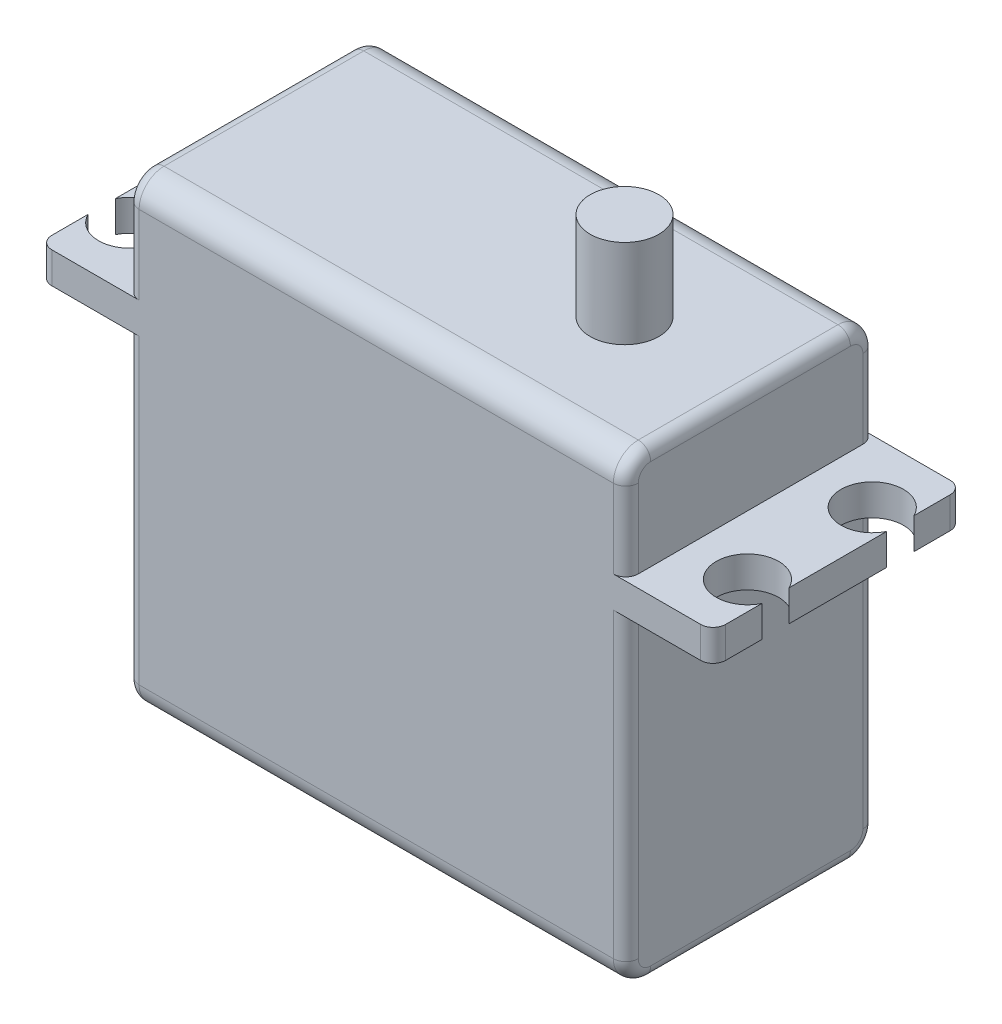
SolidWorks part; units mm, degrees
ref_plane "Front Plane" through (0, 0, 0) normal (0, 0, 1) x (1, 0, 0)
ref_plane "Top Plane" through (0, 0, 0) normal (0, 1, 0) x (1, 0, 0)
ref_plane "Right Plane" through (0, 0, 0) normal (1, 0, 0) x (0, 0, -1)
sketch "Sketch2" plane through (0, 0, 0) normal (0, 1, 0) x (1, 0, 0)
  line L1 (0, 0) -> (40, 0)
  line L2 (0, 0) -> (0, 20)
  line L3 (0, 20) -> (40, 20)
  line L4 (40, 0) -> (40, 20)
  dimension "D1" = 20
  dimension "D2" = 40
extrude "Boss-Extrude1" add sketch "Sketch2" along normal blind 37
sketch "Sketch3" plane through (0, 0, 0) normal (-1, 0, 0) x (0, 0, 1)
  line L0 (-20, 28.7) -> (0, 28.7)
  line L1 (-20, 37) -> (-20, 0) construction
  line L2 (0, 37) -> (0, 0) construction
  line L3 (0, 28.7) -> (0, 26.2)
  line L4 (0, 26.2) -> (-20, 26.2)
  line L5 (-20, 26.2) -> (-20, 28.7)
  line L6 (-20, 0) -> (0, 0) construction
  dimension "D1" = 28.7
  dimension "D2" = 2.5
extrude "Boss-Extrude2" add sketch "Sketch3" along normal blind 7
ref_plane "Plane1" through (20, 0, 0) normal (-1, 0, 0) x (0, 0, 1)
mirror "Mirror1" about plane through (20, 0, 0) normal (-1, 0, 0) of "Boss-Extrude2"
sketch "Sketch4" plane through (0, 28.7, 0) normal (0, 1, 0) x (1, 0, 0)
  line L0 (-7, 10) -> (47, 10) construction
  line L1 (-7, 0) -> (-7, 20) construction
  line L2 (47, 0) -> (47, 20) construction
  line L3 (20, 20) -> (20, 0) construction
  line L4 (40, 20) -> (0, 20) construction
  line L6 (0, 0) -> (40, 0) construction
  circle A0 centre (-4.75, 15) radius 2.5
  circle A1 centre (-4.75, 5) radius 2.5
  circle A2 centre (44.75, 5) radius 2.5
  circle A3 centre (44.75, 15) radius 2.5
  dimension "D1" = 5
  dimension "D2" = 10
  dimension "D3" = 49.5
extrude "Cut-Extrude5" cut sketch "Sketch4" against normal blind 7.25
sketch "Sketch5" plane through (0, 37, 0) normal (0, 1, 0) x (1, 0, 0)
  line L0 (0, 10) -> (40, 10) construction
  line L1 (0, 20) -> (0, 0) construction
  line L2 (40, 0) -> (40, 20) construction
  circle A0 centre (29.9, 10) radius 2.75
  dimension "D2" = 5.5
  dimension "D1" = 29.9
extrude "Boss-Extrude4" add sketch "Sketch5" along normal blind 7.1
fillet "Fillet1" radius 2 4 edges at (20, 37, 0) (20, 37, -20) (20, 0, 0) (20, 0, -20)
fillet "Fillet2" radius 1 24 edges at (40, 14.1, 0) (40, 0.5858, -0.5858) (40, 14.1, -20) (40, 0.5858, -19.4142) (40, 31.85, 0) (40, 36.4142, -0.5858) (40, 31.85, -20) (40, 36.4142, -19.4142) (0, 14.1, -20) (0, 0.5858, -19.4142) (0, 14.1, 0) (0, 0.5858, -0.5858) (0, 31.85, -20) (0, 36.4142, -19.4142) (0, 31.85, 0) (0, 36.4142, -0.5858) (40, 0, -10) (40, 37, -10) (47, 27.45, -20) (47, 27.45, 0) (0, 0, -10) (0, 37, -10) (-7, 27.45, 0) (-7, 27.45, -20)
